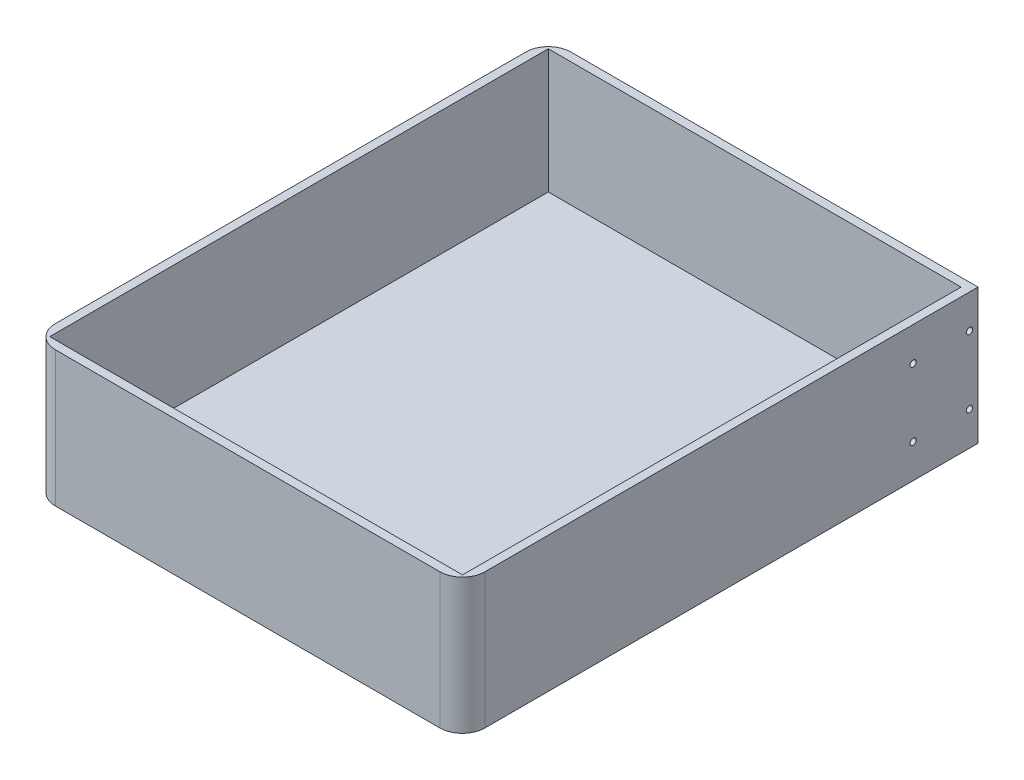
SolidWorks part; units mm, degrees
ref_plane "Front Plane" through (0, 0, 0) normal (0, 0, 1) x (1, 0, 0)
ref_plane "Top Plane" through (0, 0, 0) normal (0, 1, 0) x (1, 0, 0)
ref_plane "Right Plane" through (0, 0, 0) normal (1, 0, 0) x (0, 0, -1)
sketch "Sketch1" plane through (0, 0, 0) normal (0, 1, 0) x (1, 0, 0)
  line L1 (0, 0) -> (381, 0)
  line L2 (0, 0) -> (0, 457.2)
  line L3 (0, 457.2) -> (381, 457.2)
  line L4 (381, 0) -> (381, 457.2)
  line L5 (7.5, 7.6) -> (373.5, 7.6)
  line L6 (7.5, 7.6) -> (7.5, 449.7)
  line L7 (7.5, 449.7) -> (373.5, 449.7)
  line L8 (373.5, 7.6) -> (373.5, 449.7)
  dimension "D1" = 457.2
  dimension "D2" = 381
  dimension "D3" = 7.5
  dimension "D4" = 7.5
  dimension "D5" = 7.6
  dimension "D6" = 7.5
extrude "Boss-Extrude1" add sketch "Sketch1" along normal blind 120
sketch "Sketch2" plane through (0, 0, 0) normal (0, -1, 0) x (1, 0, 0)
  line L5 (7.5, -449.7) -> (373.5, -449.7)
  line L6 (7.5, -449.7) -> (7.5, -7.6)
  line L7 (7.5, -7.6) -> (373.5, -7.6)
  line L8 (373.5, -449.7) -> (373.5, -7.6)
extrude "Boss-Extrude2" add sketch "Sketch2" against normal blind 10
fillet "Fillet1" radius 20 3 edges at (0, 60, 0) (0, 60, -457.2) (381, 60, 0)
sketch "Sketch3" plane through (381, 0, 0) normal (1, 0, 0) x (0, 0, -1)
  line L1 (399.7, 90) -> (449.7, 90)
  line L2 (399.7, 90) -> (399.7, 30)
  line L3 (399.7, 30) -> (449.7, 30)
  line L4 (449.7, 90) -> (449.7, 30)
  line L6 (20, 120) -> (457.2, 120) construction
  line L8 (457.2, 120) -> (457.2, 0) construction
  circle A0 centre (399.7, 90) radius 2.75
  circle A1 centre (399.7, 30) radius 2.75
  circle A2 centre (449.7, 30) radius 2.75
  circle A3 centre (449.7, 90) radius 2.75
  dimension "D3" = 30
  dimension "D1" = 60
  dimension "D2" = 50
  dimension "D4" = 7.5
extrude "Cut-Extrude1" cut sketch "Sketch3" against normal blind 10 contours L1 A0 L2 | L2 A0 L1 | L4 A3 L1 | L1 A3 L4 | L3 A2 L4 | L4 A2 L3 | L2 A1 L3 | L3 A1 L2
